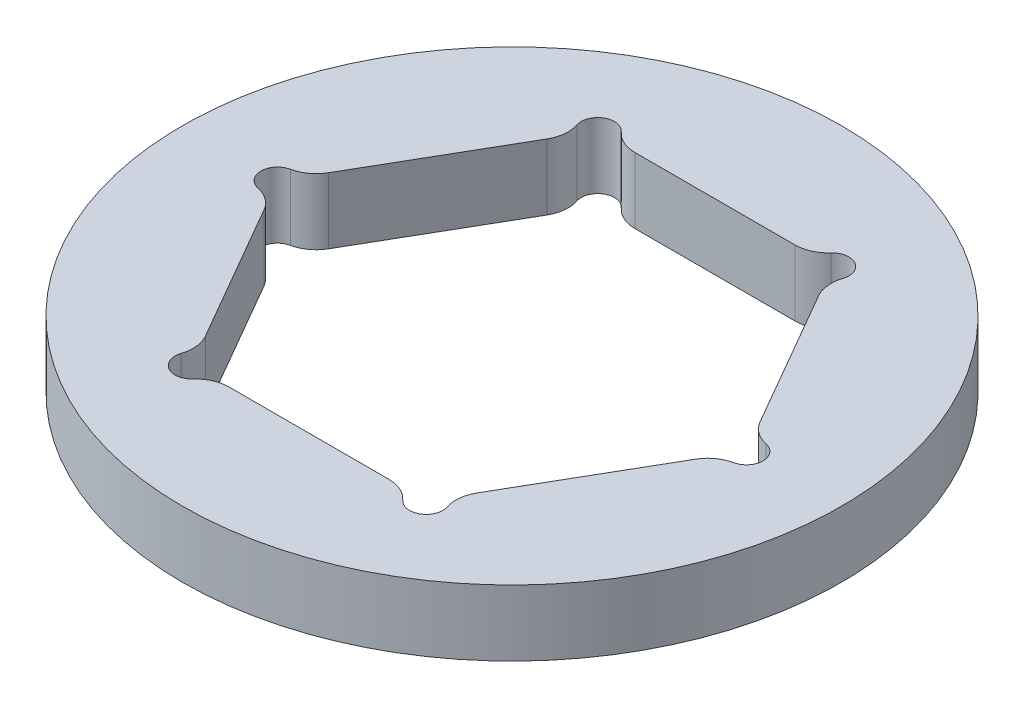
SolidWorks part; units mm, degrees
material "ABS"
ref_plane "Alzado" through (0, 0, 0) normal (0, 0, 1) x (1, 0, 0)
ref_plane "Planta" through (0, 0, 0) normal (0, 1, 0) x (1, 0, 0)
ref_plane "Vista lateral" through (0, 0, 0) normal (1, 0, 0) x (0, 0, -1)
sketch "Croquis1" plane through (0, 0, 0) normal (0, 1, 0) x (1, 0, 0)
  line L1 (3.2702, -4.1149) -> (5.1987, -0.7746)
  line L2 (5.1987, 0.7746) -> (3.2702, 4.1149)
  line L3 (1.9285, 4.8895) -> (-1.9285, 4.8895)
  line L4 (-3.2702, 4.1149) -> (-5.1987, 0.7746)
  line L5 (-5.1987, -0.7746) -> (-3.2702, -4.1149)
  line L6 (-1.9285, -4.8895) -> (1.9285, -4.8895)
  circle A0 centre (0, 0) radius 7.9375
  circle A1 centre (0, 0) radius 4.8895 construction
  arc A2 (-2.5248, 5.1562) -> (-3.203, 4.7646) centre (-2.823, 4.8895) ccw
  arc A3 (-2.5248, 5.1562) -> (-1.9285, 4.8895) centre (-1.9285, 5.6895) ccw
  arc A4 (-3.2702, 4.1149) -> (-3.203, 4.7646) centre (-3.963, 4.5149) ccw
  arc A5 (3.203, 4.7646) -> (2.5248, 5.1562) centre (2.823, 4.8895) ccw
  arc A6 (3.203, 4.7646) -> (3.2702, 4.1149) centre (3.963, 4.5149) ccw
  arc A7 (1.9285, 4.8895) -> (2.5248, 5.1562) centre (1.9285, 5.6895) ccw
  arc A8 (5.7278, -0.3915) -> (5.7278, 0.3915) centre (5.6459, 0) ccw
  arc A9 (5.7278, -0.3915) -> (5.1987, -0.7746) centre (5.8915, -1.1746) ccw
  arc A10 (5.1987, 0.7746) -> (5.7278, 0.3915) centre (5.8915, 1.1746) ccw
  arc A11 (2.5248, -5.1562) -> (3.203, -4.7646) centre (2.823, -4.8895) ccw
  arc A12 (2.5248, -5.1562) -> (1.9285, -4.8895) centre (1.9285, -5.6895) ccw
  arc A13 (3.2702, -4.1149) -> (3.203, -4.7646) centre (3.963, -4.5149) ccw
  arc A14 (-3.203, -4.7646) -> (-2.5248, -5.1562) centre (-2.823, -4.8895) ccw
  arc A15 (-3.203, -4.7646) -> (-3.2702, -4.1149) centre (-3.963, -4.5149) ccw
  arc A16 (-1.9285, -4.8895) -> (-2.5248, -5.1562) centre (-1.9285, -5.6895) ccw
  arc A17 (-5.7278, 0.3915) -> (-5.7278, -0.3915) centre (-5.6459, 0) ccw
  arc A18 (-5.7278, 0.3915) -> (-5.1987, 0.7746) centre (-5.8915, 1.1746) ccw
  arc A19 (-5.1987, -0.7746) -> (-5.7278, -0.3915) centre (-5.8915, -1.1746) ccw
  dimension "D2" = 15.875
  dimension "D3" = 0.8
  dimension "D4" = 0.8
  dimension "D1" = 9.779
  dimension "D5" = 6
extrude "Saliente-Extruir1" add sketch "Croquis1" along normal mid plane 1.5875
